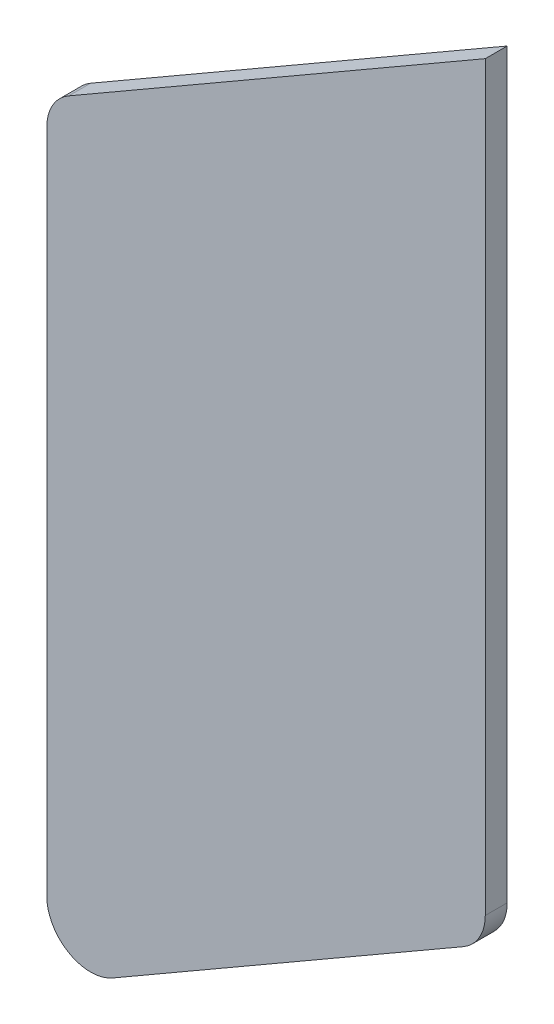
SolidWorks part; units mm, degrees
material "1.0037 (S235JR)"
ref_plane "Plan de face" through (0, 0, 0) normal (0, 0, 1) x (1, 0, 0)
ref_plane "Plan de dessus" through (0, 0, 0) normal (0, 1, 0) x (1, 0, 0)
ref_plane "Plan de droite" through (0, 0, 0) normal (1, 0, 0) x (0, 0, -1)
sketch "Esquisse1" plane through (0, 0, 0) normal (0, 0, 1) x (1, 0, 0)
  line L0 (47.5, 139.4615) -> (47.5, -29.765)
  line L5 (47.5, 139.4615) -> (-47.5, 84.6132)
  line L6 (42.5, -38.4252) -> (-37.5, -84.6132)
  line L7 (-52.5, 75.953) -> (-52.5, -75.953)
  line L8 (-52.5, 81.7265) -> (-52.5, 57.5041) construction
  arc A0 (-47.5, 84.6132) -> (-52.5, 75.953) centre (-42.5, 75.953) ccw
  arc A1 (-37.5, -84.6132) -> (-52.5, -75.953) centre (-42.5, -75.953) cw
  arc A2 (47.5, -29.765) -> (42.5, -38.4252) centre (37.5, -29.765) cw
  point P0 (-52.5, 0)
  point P5 (0, 112.0374)
  point P6 (2.5, -61.5192)
  point P13 (-52.5, -93.2735)
  dimension "D4" = 10
  dimension "D5" = 10
  dimension "D1" = 100
  dimension "D2" = 175
  dimension "D3" = 60
extrude "Boss.-Extru.1" add sketch "Esquisse1" along normal blind 5 contours L5 A0 L7 A1 L6 A2 L0
